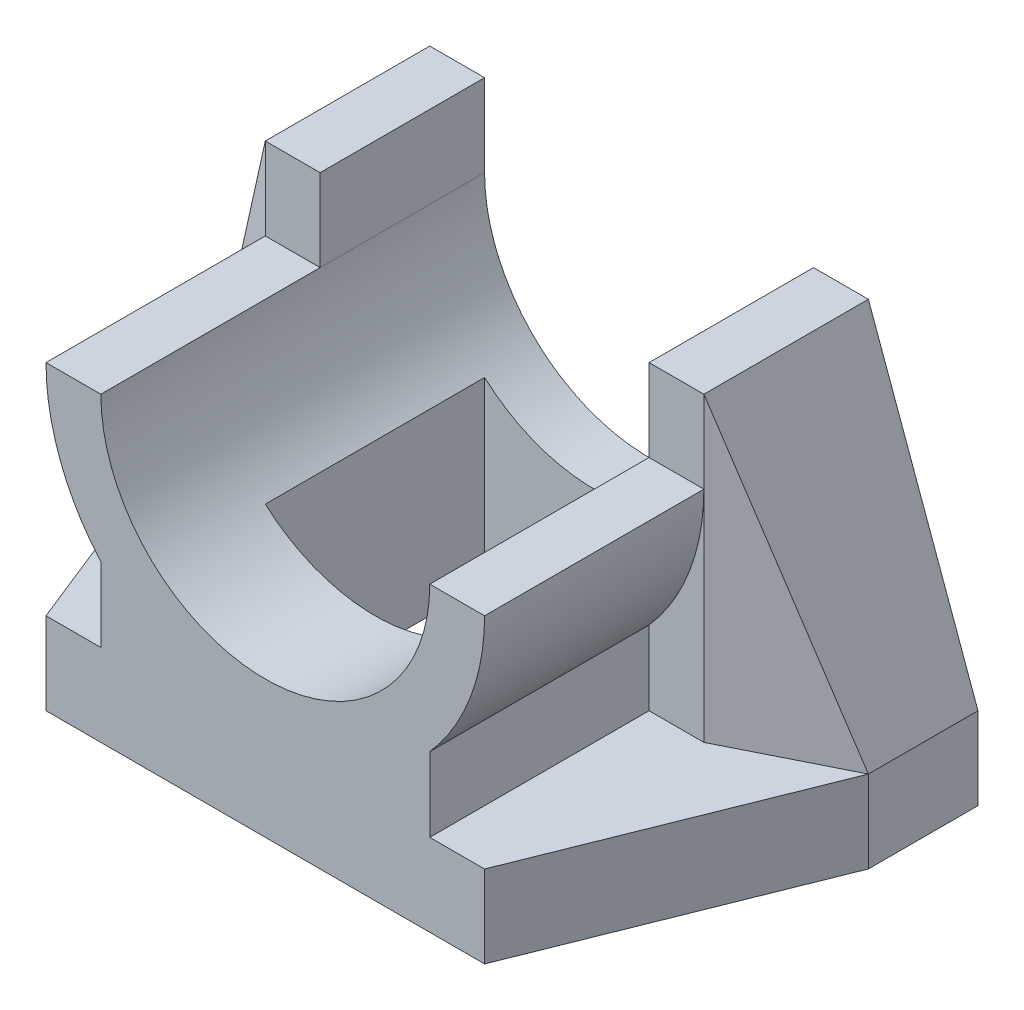
SolidWorks part; units mm, degrees
ref_plane "Front Plane" through (0, 0, 0) normal (0, 0, 1) x (1, 0, 0)
ref_plane "Top Plane" through (0, 0, 0) normal (0, 1, 0) x (1, 0, 0)
ref_plane "Right Plane" through (0, 0, 0) normal (1, 0, 0) x (0, 0, -1)
sketch "Sketch1" plane through (0, 0, 0) normal (0, 1, 0) x (1, 0, 0)
  line L0 (0, 0) -> (0, -70) construction
  line L1 (-40, 0) -> (40, 0)
  line L2 (40, 0) -> (40, -70)
  line L3 (40, -70) -> (-40, -70)
  line L4 (-40, -70) -> (-40, 0)
  dimension "D1" = 80
  dimension "D2" = 70
extrude "Boss-Extrude1" add sketch "Sketch1" along normal blind 15
sketch "Sketch2" plane through (0, 0, 0) normal (0, 0, 1) x (1, 0, 0)
  line L0 (0, 15) -> (0, 70) construction
  line L1 (-30, 15) -> (30, 15)
  line L2 (30, 15) -> (30, 28.5425)
  line L3 (40, 55) -> (-40, 55)
  line L4 (-30, 28.5425) -> (-30, 15)
  arc A0 (30, 28.5425) -> (40, 55) centre (0, 55) ccw
  arc A1 (-40, 55) -> (-30, 28.5425) centre (0, 55) ccw
  dimension "D2" = 40
  dimension "D1" = 60
extrude "Boss-Extrude2" add sketch "Sketch2" along normal blind 70
sketch "Sketch3" plane through (0, 0, 0) normal (0, 1, 0) x (1, 0, 0)
  line L0 (-60, 0) -> (-40, 0)
  line L1 (-40, 0) -> (-40, -70)
  line L2 (-40, -70) -> (-60, -70)
  line L3 (-60, -70) -> (-60, 0)
  dimension "D1" = 20
  dimension "D2" = 70
extrude "Boss-Extrude3" add sketch "Sketch3" along normal blind 15
sketch "Sketch4" plane through (0, 0, 0) normal (0, 0, 1) x (1, 0, 0)
  line L0 (-40, 55) -> (-30, 55)
  line L1 (-30, 55) -> (-30, 70)
  line L2 (-30, 70) -> (-40, 70)
  line L3 (-40, 70) -> (-40, 55)
  dimension "D1" = 10
  dimension "D2" = 15
extrude "Boss-Extrude4" add sketch "Sketch4" along normal blind 30
sketch "Sketch5" plane through (0, 0, 0) normal (0, 0, 1) x (1, 0, 0)
  line L0 (-60, 15) -> (-40, 70)
  line L1 (-40, 70) -> (-40, 55)
  line L2 (-40, 55) -> (-30, 55)
  line L3 (-30, 55) -> (-30, 15)
  line L4 (-30, 15) -> (-60, 15)
  dimension "D1" = 15
  dimension "D2" = 10
  dimension "D3" = 30
extrude "Boss-Extrude5" add sketch "Sketch5" along normal blind 30
sketch "Sketch6" plane through (0, 0, 0) normal (0, 1, 0) x (1, 0, 0)
  line L0 (-60, -20) -> (-40, -70)
  line L1 (-40, -70) -> (-60, -70)
  line L2 (-60, -70) -> (-60, -20)
  dimension "D1" = 20
  dimension "D2" = 50
extrude "Cut-Extrude1" cut sketch "Sketch6" along normal blind 15
sketch "Sketch7" plane through (0, 0, 0) normal (0, 1, 0) x (1, 0, 0)
  line L0 (-60, -20) -> (-40, -30)
  line L1 (-40, -30) -> (-60, -30)
  line L2 (-60, -30) -> (-60, -20)
  dimension "D1" = 20
  dimension "D2" = 10
extrude "Cut-Extrude2" cut sketch "Sketch7" along normal blind 60 from offset 15
mirror "Mirror1" about plane through (0, 0, 0) normal (1, 0, 0) of "Cut-Extrude2", "Cut-Extrude1", "Boss-Extrude5", "Boss-Extrude4", "Boss-Extrude3"
sketch "Sketch8" plane through (0, 0, 0) normal (0, 0, 1) x (1, 0, 0)
  line L0 (0, 20) -> (0, 75) construction
  line L1 (-30, 72) -> (-30, 55)
  line L2 (30, 55) -> (30, 72)
  line L3 (30, 72) -> (-30, 72)
  arc A0 (-30, 55) -> (30, 55) centre (0, 55) ccw
  dimension "D1" = 30
  dimension "D2" = 60
extrude "Cut-Extrude3" cut sketch "Sketch8" against normal through all and the other way through all
sketch "Sketch9" plane through (0, 0, 0) normal (0, 1, 0) x (1, 0, 0)
  line L0 (0, 0) -> (0, -70) construction
  line L1 (-20, -10) -> (20, -10)
  line L2 (20, -10) -> (20, -50)
  line L3 (20, -50) -> (-20, -50)
  line L4 (-20, -50) -> (-20, -10)
  dimension "D1" = 40
  dimension "D2" = 40
extrude "Cut-Extrude4" cut sketch "Sketch9" against normal through all and the other way through all
